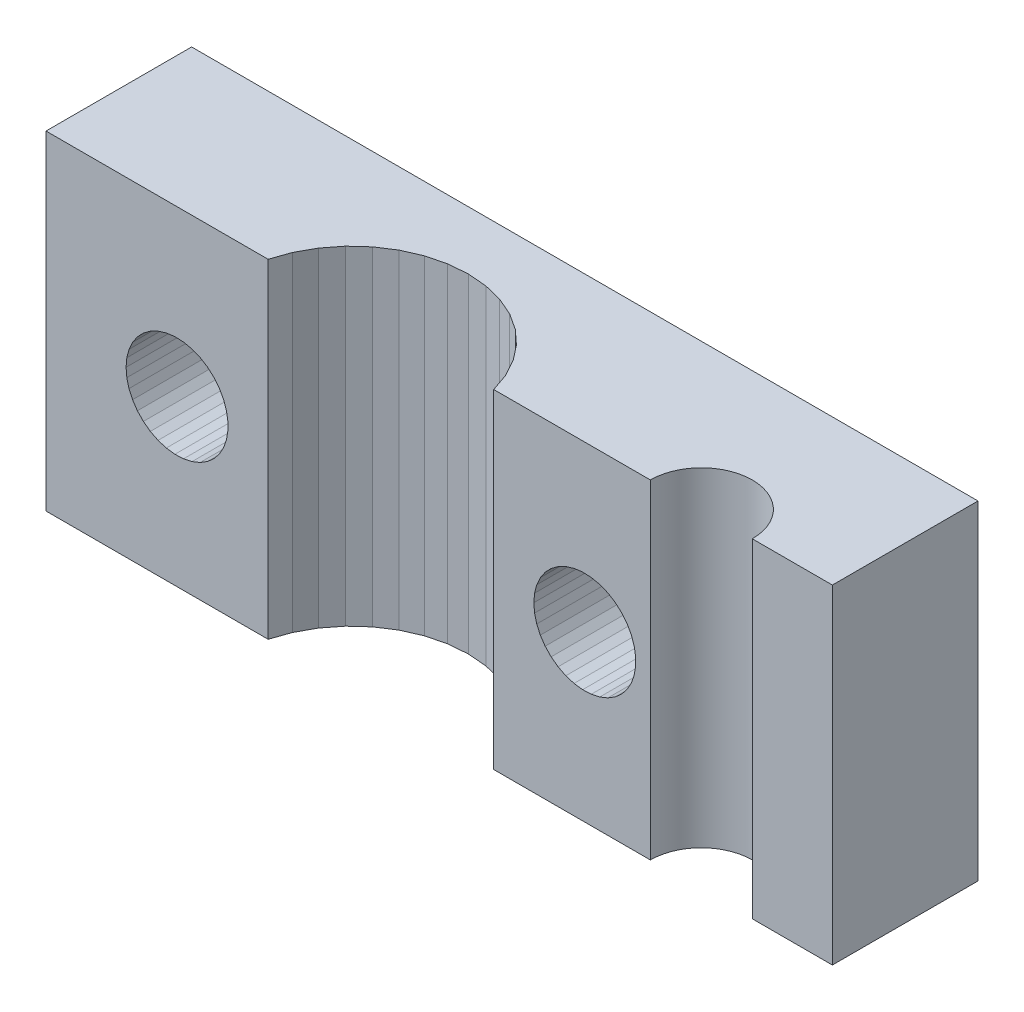
SolidWorks part; units mm, degrees
ref_plane "Plan de face" through (0, 0, 0) normal (0, 0, 1) x (1, 0, 0)
ref_plane "Plan de dessus" through (0, 0, 0) normal (0, 1, 0) x (1, 0, 0)
ref_plane "Plan de droite" through (0, 0, 0) normal (1, 0, 0) x (0, 0, -1)
ref_plane "Plan1" through (0, 0, 0) normal (0, 0, -1) x (-1, 0, 0)
sketch "Esquisse1" plane through (0, 0, 0) normal (0, 0, -1) x (-1, 0, 0)
  line L0 (-27, 11.3) -> (-27, 0)
  line L1 (-27, 0) -> (0, 0)
  line L2 (0, 0) -> (0, 11.3)
  line L3 (0, 11.3) -> (-27, 11.3)
extrude "Boss.-Extru.1" add sketch "Esquisse1" against normal blind 5
sketch "Esquisse2" plane through (0, 11.3, 0) normal (0, 1, 0) x (-1, 0, 0)
  line L0 (-15.373, 5) -> (-15.373, 4.7747)
  line L1 (-15.373, 4.7747) -> (-14.841, 3.8005)
  line L2 (-14.841, 3.8005) -> (-14.435, 3.2823)
  line L3 (-14.435, 3.2823) -> (-13.9495, 2.8377)
  line L4 (-13.9495, 2.8377) -> (-13.3976, 2.4788)
  line L5 (-13.3976, 2.4788) -> (-12.7944, 2.2152)
  line L6 (-12.7944, 2.2152) -> (-12.1561, 2.0542)
  line L7 (-12.1561, 2.0542) -> (-11.5, 2)
  line L8 (-11.5, 2) -> (-10.8439, 2.0542)
  line L9 (-10.8439, 2.0542) -> (-10.2056, 2.2152)
  line L10 (-10.2056, 2.2152) -> (-9.6024, 2.4788)
  line L11 (-9.6024, 2.4788) -> (-9.0505, 2.8377)
  line L12 (-9.0505, 2.8377) -> (-8.565, 3.2823)
  line L13 (-8.565, 3.2823) -> (-8.159, 3.8005)
  line L14 (-8.159, 3.8005) -> (-7.627, 4.7747)
  line L15 (-7.627, 4.7747) -> (-7.627, 5)
  line L16 (-7.627, 5) -> (-15.373, 5)
extrude "Enlèv. mat.-Extru.1" cut sketch "Esquisse2" against normal through all
sketch "Esquisse3" plane through (0, 11.3, 0) normal (0, 1, 0) x (-1, 0, 0)
  line L0 (-20.75, 5) -> (-24.25, 5)
  arc A0 (-24.25, 5) -> (-20.75, 5) centre (-22.5, 5) ccw
  dimension "D1" = 3.5
extrude "Enlèv. mat.-Extru.2" cut sketch "Esquisse3" against normal through all
sketch "Esquisse4" plane through (0, 0, 0) normal (0, 0, -1) x (-1, 0, 0)
  line L0 (-2.75, 5.65) -> (-2.7752, 5.9458)
  line L1 (-2.7752, 5.9458) -> (-2.85, 6.233)
  line L2 (-2.85, 6.233) -> (-2.9722, 6.5035)
  line L3 (-2.9722, 6.5035) -> (-3.1384, 6.7494)
  line L4 (-3.1384, 6.7494) -> (-3.3438, 6.9637)
  line L5 (-3.3438, 6.9637) -> (-3.5825, 7.1402)
  line L6 (-3.5825, 7.1402) -> (-3.8475, 7.2738)
  line L7 (-3.8475, 7.2738) -> (-4.1313, 7.3607)
  line L8 (-4.1313, 7.3607) -> (-4.4257, 7.3984)
  line L9 (-4.4257, 7.3984) -> (-4.7223, 7.3858)
  line L10 (-4.7223, 7.3858) -> (-5.0124, 7.3233)
  line L11 (-5.0124, 7.3233) -> (-5.2879, 7.2126)
  line L12 (-5.2879, 7.2126) -> (-5.5406, 7.057)
  line L13 (-5.5406, 7.057) -> (-5.7634, 6.8609)
  line L14 (-5.7634, 6.8609) -> (-5.9499, 6.63)
  line L15 (-5.9499, 6.63) -> (-6.0946, 6.3708)
  line L16 (-6.0946, 6.3708) -> (-6.1935, 6.091)
  line L17 (-6.1935, 6.091) -> (-6.2437, 5.7984)
  line L18 (-6.2437, 5.7984) -> (-6.25, 5.65)
  line L19 (-6.25, 5.65) -> (-6.2437, 5.5016)
  line L20 (-6.2437, 5.5016) -> (-6.1935, 5.209)
  line L21 (-6.1935, 5.209) -> (-6.0946, 4.9292)
  line L22 (-6.0946, 4.9292) -> (-5.9499, 4.67)
  line L23 (-5.9499, 4.67) -> (-5.7634, 4.4391)
  line L24 (-5.7634, 4.4391) -> (-5.5406, 4.243)
  line L25 (-5.5406, 4.243) -> (-5.2879, 4.0874)
  line L26 (-5.2879, 4.0874) -> (-5.0124, 3.9767)
  line L27 (-5.0124, 3.9767) -> (-4.7223, 3.9142)
  line L28 (-4.7223, 3.9142) -> (-4.4257, 3.9016)
  line L29 (-4.4257, 3.9016) -> (-4.1313, 3.9393)
  line L30 (-4.1313, 3.9393) -> (-3.8475, 4.0262)
  line L31 (-3.8475, 4.0262) -> (-3.5825, 4.1598)
  line L32 (-3.5825, 4.1598) -> (-3.3438, 4.3363)
  line L33 (-3.3438, 4.3363) -> (-3.1384, 4.5506)
  line L34 (-3.1384, 4.5506) -> (-2.9722, 4.7965)
  line L35 (-2.9722, 4.7965) -> (-2.85, 5.067)
  line L36 (-2.85, 5.067) -> (-2.7752, 5.3542)
  line L37 (-2.7752, 5.3542) -> (-2.75, 5.65)
extrude "Enlèv. mat.-Extru.3" cut sketch "Esquisse4" against normal through all
sketch "Esquisse5" plane through (0, 0, 5) normal (0, 0, 1) x (1, 0, 0)
  line L0 (16.7752, 5.3542) -> (16.85, 5.067)
  line L1 (16.85, 5.067) -> (16.9722, 4.7965)
  line L2 (16.9722, 4.7965) -> (17.1384, 4.5506)
  line L3 (17.1384, 4.5506) -> (17.3438, 4.3363)
  line L4 (17.3438, 4.3363) -> (17.5825, 4.1598)
  line L5 (17.5825, 4.1598) -> (17.8475, 4.0262)
  line L6 (17.8475, 4.0262) -> (18.1313, 3.9393)
  line L7 (18.1313, 3.9393) -> (18.4257, 3.9016)
  line L8 (18.4257, 3.9016) -> (18.7223, 3.9142)
  line L9 (18.7223, 3.9142) -> (19.0124, 3.9767)
  line L10 (19.0124, 3.9767) -> (19.2879, 4.0874)
  line L11 (19.2879, 4.0874) -> (19.5406, 4.243)
  line L12 (19.5406, 4.243) -> (19.7634, 4.4391)
  line L13 (19.7634, 4.4391) -> (19.9499, 4.67)
  line L14 (19.9499, 4.67) -> (20.0947, 4.9292)
  line L15 (20.0947, 4.9292) -> (20.1935, 5.209)
  line L16 (20.1935, 5.209) -> (20.2437, 5.5016)
  line L17 (20.2437, 5.5016) -> (20.2437, 5.7984)
  line L18 (20.2437, 5.7984) -> (20.1935, 6.091)
  line L19 (20.1935, 6.091) -> (20.0947, 6.3708)
  line L20 (20.0947, 6.3708) -> (19.9499, 6.63)
  line L21 (19.9499, 6.63) -> (19.7634, 6.8609)
  line L22 (19.7634, 6.8609) -> (19.5406, 7.057)
  line L23 (19.5406, 7.057) -> (19.2879, 7.2126)
  line L24 (19.2879, 7.2126) -> (19.0124, 7.3233)
  line L25 (19.0124, 7.3233) -> (18.7223, 7.3858)
  line L26 (18.7223, 7.3858) -> (18.4257, 7.3984)
  line L27 (18.4257, 7.3984) -> (18.1313, 7.3607)
  line L28 (18.1313, 7.3607) -> (17.8475, 7.2738)
  line L29 (17.8475, 7.2738) -> (17.5825, 7.1402)
  line L30 (17.5825, 7.1402) -> (17.3438, 6.9637)
  line L31 (17.3438, 6.9637) -> (17.1384, 6.7494)
  line L32 (17.1384, 6.7494) -> (16.9722, 6.5035)
  line L33 (16.9722, 6.5035) -> (16.85, 6.233)
  line L34 (16.85, 6.233) -> (16.7752, 5.9458)
  line L35 (16.7752, 5.9458) -> (16.75, 5.65)
  line L36 (16.75, 5.65) -> (16.7752, 5.3542)
extrude "Enlèv. mat.-Extru.4" cut sketch "Esquisse5" against normal through all
draft "Dépouille1" type of draft neutral plane draft angle 19.198 faces to draft 1 face at (7.627, 5.65, 4.8874) neutral plane through (0, 0, 5) neutral plane normal (0, 0, 1) parameters "D1"=19.198
draft "Dépouille2" type of draft neutral plane draft angle 19.198 faces to draft 1 face at (15.373, 5.65, 4.8874) neutral plane through (0, 0, 5) neutral plane normal (0, 0, 1) parameters "D1"=19.198
